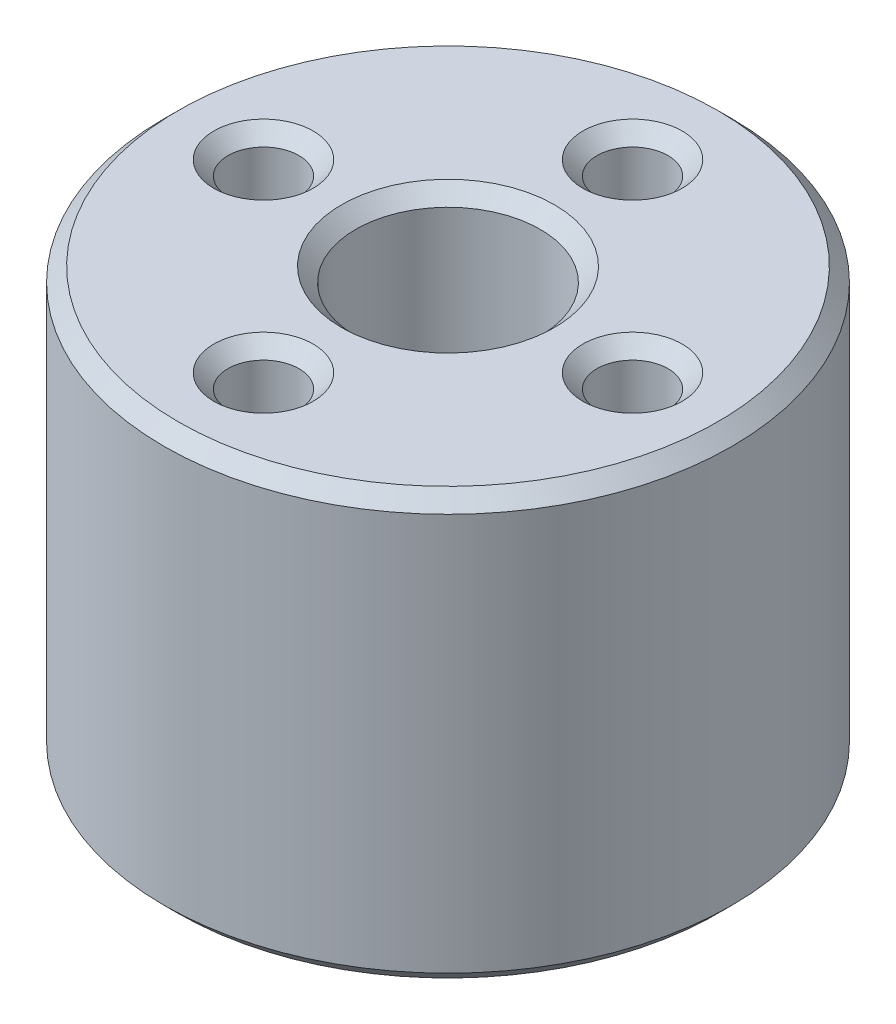
SolidWorks part; units mm, degrees
ref_plane "前视基准面" through (0, 0, 0) normal (0, 0, 1) x (1, 0, 0)
ref_plane "上视基准面" through (0, 0, 0) normal (0, 1, 0) x (1, 0, 0)
ref_plane "右视基准面" through (0, 0, 0) normal (1, 0, 0) x (0, 0, -1)
other "Configuration Table"
sketch "草图1" plane through (0, 0, 0) normal (0, 1, 0) x (1, 0, 0)
  circle A0 centre (0, 0) radius 10
  circle A1 centre (0, 0) radius 3.25
  dimension "D1" = 20
  dimension "D2" = 6.5
extrude "凸台-拉伸1" add sketch "草图1" along normal blind 15
sketch "草图2" plane through (0, 15, 0) normal (0, 1, 0) x (1, 0, 0)
  circle A0 centre (-6.5, 0) radius 1.25
  dimension "D1" = 2.5
  dimension "D2" = 6.5
extrude "切除-拉伸1" cut sketch "草图2" against normal blind 15
pattern_circular "阵列(圆周)1" count 4 over 360 about axis through (0, 0, 0) along (0, 1, 0) of "切除-拉伸1"
chamfer "倒角1" distance 0.5 angle 45 12 edges at (0, 0, 10) (0, 15, 10) (-1.25, 15, -6.5) (-1.25, 0, -6.5) (6.5, 15, -1.25) (6.5, 0, -1.25) (0, 0, 3.25) (0, 15, 3.25) (1.25, 15, 6.5) (1.25, 0, 6.5) (-6.5, 15, 1.25) (-6.5, 0, 1.25)
